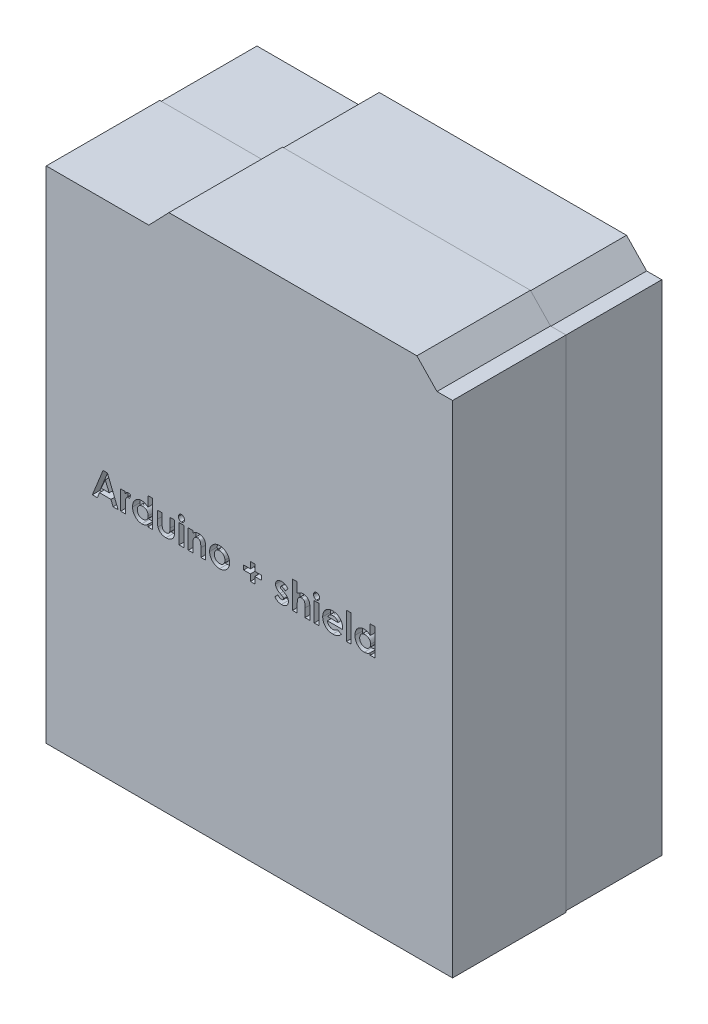
SolidWorks part; units mm, degrees
ref_plane "Front Plane" through (0, 0, 0) normal (0, 0, 1) x (1, 0, 0)
ref_plane "Top Plane" through (0, 0, 0) normal (0, 1, 0) x (1, 0, 0)
ref_plane "Right Plane" through (0, 0, 0) normal (1, 0, 0) x (0, 0, -1)
sketch "Sketch1" plane through (0, 0, 0) normal (0, 0, 1) x (1, 0, 0)
  line L0 (-26.75, 32.95) -> (-13.25, 32.95)
  line L1 (-26.75, -32.95) -> (26.75, -32.95)
  line L2 (-26.75, -32.95) -> (-26.75, 32.95)
  line L3 (-26.75, 32.95) -> (26.75, 32.95) construction
  line L4 (26.75, -32.95) -> (26.75, 32.95)
  line L5 (-26.75, -32.95) -> (26.75, 32.95) construction
  line L6 (-26.75, 32.95) -> (26.75, -32.95) construction
  line L7 (-13.25, 32.95) -> (-10.595, 35.71)
  line L8 (-10.595, 35.71) -> (22.095, 35.71)
  line L10 (-26.75, -23.5649) -> (26.75, -23.5649) construction
  line L11 (22.095, 35.71) -> (24.75, 32.95)
  line L12 (24.75, 32.95) -> (26.75, 32.95)
  circle A0 centre (19.45, 32.95) radius 1.5
  circle A1 centre (-8.75, 32.95) radius 1.5
  circle A2 centre (-24.05, -23.5649) radius 1.5
  circle A3 centre (24.05, -23.5649) radius 1.5
  point P0 (0, 0)
  dimension "D6" = 3
  dimension "D10" = 3
  dimension "D1" = 65.9
  dimension "D2" = 53.5
  dimension "D3" = 32.69
  dimension "D4" = 40
  dimension "D5" = 68.66
  dimension "D7" = 18
  dimension "D8" = 7.3
  dimension "D9" = 2
  dimension "D11" = 2.7
  dimension "D12" = 2.7
extrude "carte" add sketch "Sketch1" along normal blind 12.75
sketch "Sketch2" plane through (0, 0, 0) normal (0, 0, -1) x (-1, 0, 0)
  line L25 (-21.75, 28.8564) -> (-21.75, -27.95)
  line L26 (-21.75, -27.95) -> (21.75, -27.95)
  line L27 (21.75, -27.95) -> (21.75, 27.95)
  line L28 (21.75, 27.95) -> (11.1219, 27.95)
  line L29 (11.1219, 27.95) -> (8.4669, 30.71)
  line L30 (8.4669, 30.71) -> (-19.9669, 30.71)
  line L31 (-19.9669, 30.71) -> (-21.75, 28.8564)
  line L33 (-21.75, 28.8564) -> (-21.75, -27.95)
  line L34 (-21.75, -27.95) -> (21.75, -27.95)
  line L35 (21.75, -27.95) -> (21.75, 27.95)
  line L36 (21.75, 27.95) -> (11.1219, 27.95)
  line L37 (11.1219, 27.95) -> (8.4669, 30.71)
  line L38 (8.4669, 30.71) -> (-19.9669, 30.71)
  line L39 (-19.9669, 30.71) -> (-21.75, 28.8564)
  line L47 (-20.75, 28.4535) -> (-20.75, -26.95)
  line L48 (-20.75, -26.95) -> (20.75, -26.95)
  line L49 (20.75, -26.95) -> (20.75, 26.95)
  line L50 (20.75, 26.95) -> (10.6963, 26.95)
  line L51 (10.6963, 26.95) -> (8.0413, 29.71)
  line L52 (8.0413, 29.71) -> (-19.5413, 29.71)
  line L53 (-19.5413, 29.71) -> (-20.75, 28.4535)
  line L54 (-20.75, 28.4535) -> (-20.75, -26.95)
  line L55 (-20.75, -26.95) -> (20.75, -26.95)
  line L56 (20.75, -26.95) -> (20.75, 26.95)
  line L57 (20.75, 26.95) -> (10.6963, 26.95)
  line L58 (10.6963, 26.95) -> (8.0413, 29.71)
  line L59 (8.0413, 29.71) -> (-19.5413, 29.71)
  line L60 (-19.5413, 29.71) -> (-20.75, 28.4535)
  dimension "D1" = 5
  dimension "D2" = 6
extrude "pins" add sketch "Sketch2" along normal blind 2
sketch "Sketch3" plane through (0, 0, 12.75) normal (0, 0, 1) x (1, 0, 0)
  line L24 (26.85, 33.05) -> (24.7926, 33.05)
  line L25 (24.7926, 33.05) -> (22.1376, 35.81)
  line L26 (22.1376, 35.81) -> (-10.6376, 35.81)
  line L27 (-10.6376, 35.81) -> (-13.2926, 33.05)
  line L28 (-13.2926, 33.05) -> (-26.85, 33.05)
  line L29 (-26.85, 33.05) -> (-26.85, -33.05)
  line L30 (-26.85, -33.05) -> (26.85, -33.05)
  line L31 (26.85, -33.05) -> (26.85, 33.05)
  line L32 (26.85, 33.05) -> (24.7926, 33.05)
  line L33 (24.7926, 33.05) -> (22.1376, 35.81)
  line L34 (22.1376, 35.81) -> (-10.6376, 35.81)
  line L35 (-10.6376, 35.81) -> (-13.2926, 33.05)
  line L36 (-13.2926, 33.05) -> (-26.85, 33.05)
  line L37 (-26.85, 33.05) -> (-26.85, -33.05)
  line L38 (-26.85, -33.05) -> (26.85, -33.05)
  line L39 (26.85, -33.05) -> (26.85, 33.05)
  dimension "D1" = 0.1
extrude "Boss-Extrude3" add sketch "Sketch3" along normal blind 15
sketch "Sketch4" plane through (0, 0, 27.75) normal (0, 0, 1) x (1, 0, 0)
  text T0 "<b>Arduino + shield</b>" font "Century Gothic" height 3.5
extrude "Cut-Extrude1" cut sketch "Sketch4" against normal blind 1
